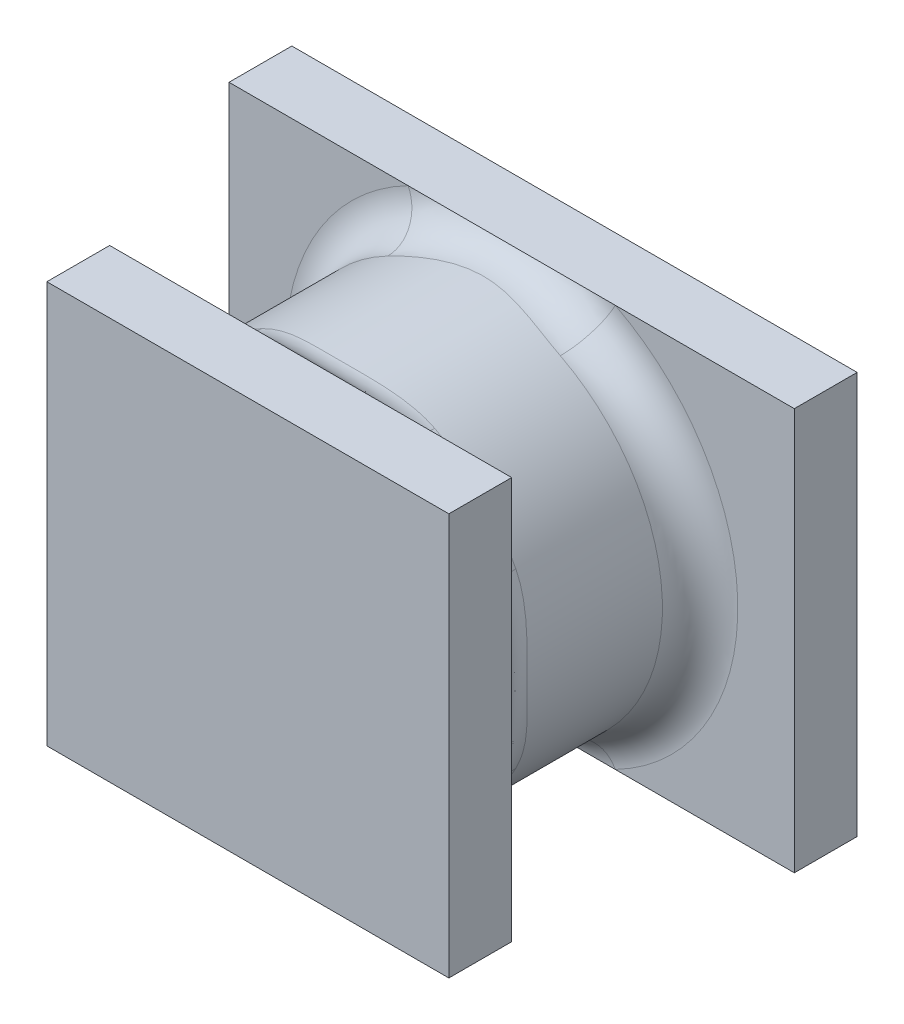
SolidWorks part; units mm, degrees
ref_plane "Спереди" through (0, 0, 0) normal (0, 0, 1) x (1, 0, 0)
ref_plane "Сверху" through (0, 0, 0) normal (0, 1, 0) x (1, 0, 0)
ref_plane "Справа" through (0, 0, 0) normal (1, 0, 0) x (0, 0, -1)
sketch "Эскиз1" plane through (0, 0, 0) normal (0, 0, 1) x (1, 0, 0)
  line L1 (-2.25, 1.6) -> (2.25, 1.6)
  line L2 (-2.25, 1.6) -> (-2.25, -1.6)
  line L3 (-2.25, -1.6) -> (2.25, -1.6)
  line L4 (2.25, 1.6) -> (2.25, -1.6)
  line L5 (-2.25, 1.6) -> (2.25, -1.6) construction
  line L6 (-2.25, -1.6) -> (2.25, 1.6) construction
  point P0 (0, 0)
  dimension "D1" = 3.2
  dimension "D2" = 4.5
extrude "Бобышка-Вытянуть1" add sketch "Эскиз1" along normal blind 0.5
sketch "Эскиз2" plane through (0, 0, 0.5) normal (0, 0, 1) x (1, 0, 0)
  circle A0 centre (0, 0) radius 1.5
  dimension "D1" = 3
extrude "Бобышка-Вытянуть2" add sketch "Эскиз2" along normal blind 1.6
sketch "Эскиз3" plane through (0, 0, 2.1) normal (0, 0, 1) x (1, 0, 0)
  line L1 (-1.6, -1.6) -> (1.6, -1.6)
  line L2 (-1.6, -1.6) -> (-1.6, 1.6)
  line L3 (-1.6, 1.6) -> (1.6, 1.6)
  line L4 (1.6, -1.6) -> (1.6, 1.6)
  line L5 (-1.6, -1.6) -> (1.6, 1.6) construction
  line L6 (-1.6, 1.6) -> (1.6, -1.6) construction
  point P0 (0, 0)
  dimension "D1" = 3.2
extrude "Бобышка-Вытянуть3" add sketch "Эскиз3" along normal blind 0.5
fillet "Скругление1" radius 0.3 1 edges at (1.5, 0, 0.5)
fillet "Скругление2" radius 0.3 1 edges at (1.5, 0, 2.1)
